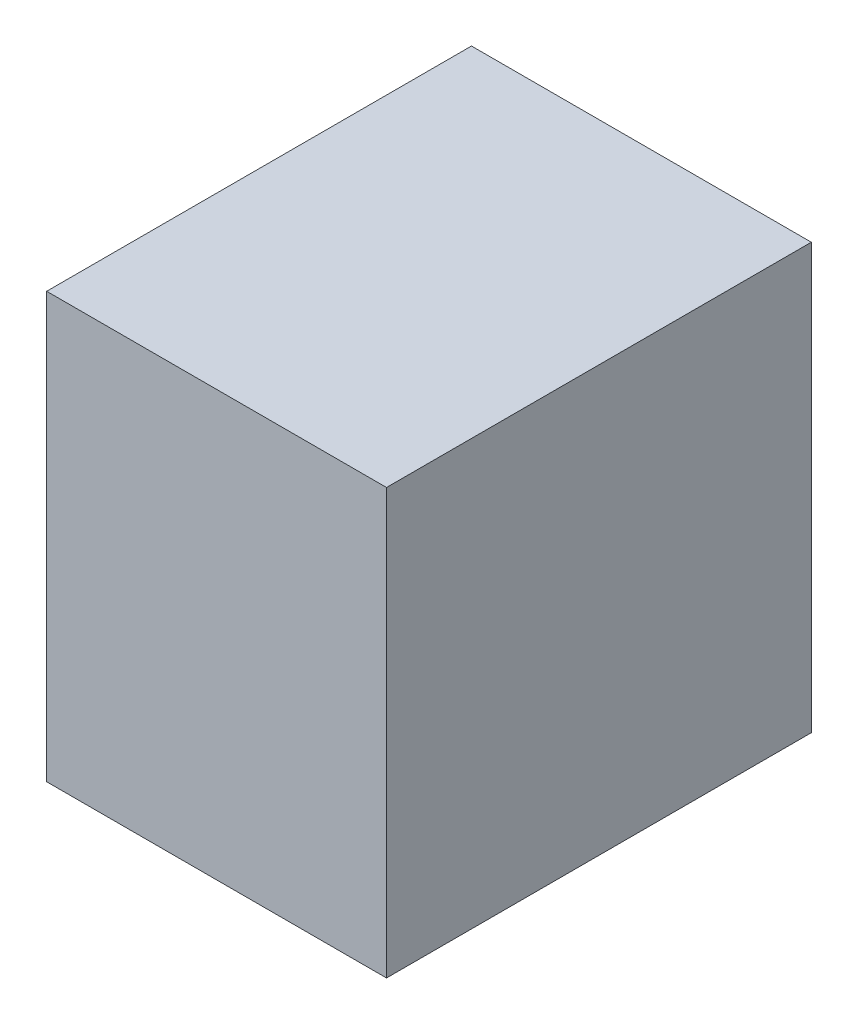
SolidWorks part; units mm, degrees
ref_plane "Front Plane" through (0, 0, 0) normal (0, 0, 1) x (1, 0, 0)
ref_plane "Top Plane" through (0, 0, 0) normal (0, 1, 0) x (1, 0, 0)
ref_plane "Right Plane" through (0, 0, 0) normal (1, 0, 0) x (0, 0, -1)
sketch "Sketch1" plane through (0, 0, 0) normal (0, 0, 1) x (1, 0, 0)
  line L1 (-11.0657, 50.2484) -> (14.3343, 50.2484)
  line L2 (-11.0657, 50.2484) -> (-11.0657, 18.4984)
  line L3 (-11.0657, 18.4984) -> (14.3343, 18.4984)
  line L4 (14.3343, 50.2484) -> (14.3343, 18.4984)
  dimension "D1" = 31.75
  dimension "D2" = 25.4
extrude "Boss-Extrude1" add sketch "Sketch1" along normal blind 31.75
sketch "Sketch2" plane through (0, 0, 31.75) normal (0, 0, 1) x (1, 0, 0)
  line L0 (-11.0657, 50.2484) -> (-11.0657, 18.4984) construction
  line L1 (14.3343, 50.2484) -> (-11.0657, 50.2484) construction
  line L2 (14.3343, 18.4984) -> (14.3343, 50.2484) construction
  line L3 (-11.0657, 18.4984) -> (14.3343, 18.4984) construction
  point P0 (-5.0657, 44.2484)
  point P1 (8.3343, 44.2484)
  point P2 (8.3343, 24.4984)
  point P3 (-5.0657, 24.4984)
  dimension "D1" = 6
  dimension "D2" = 6
  dimension "D3" = 6
  dimension "D4" = 6
  dimension "D5" = 6
  dimension "D6" = 6
  dimension "D7" = 6
  dimension "D8" = 6
